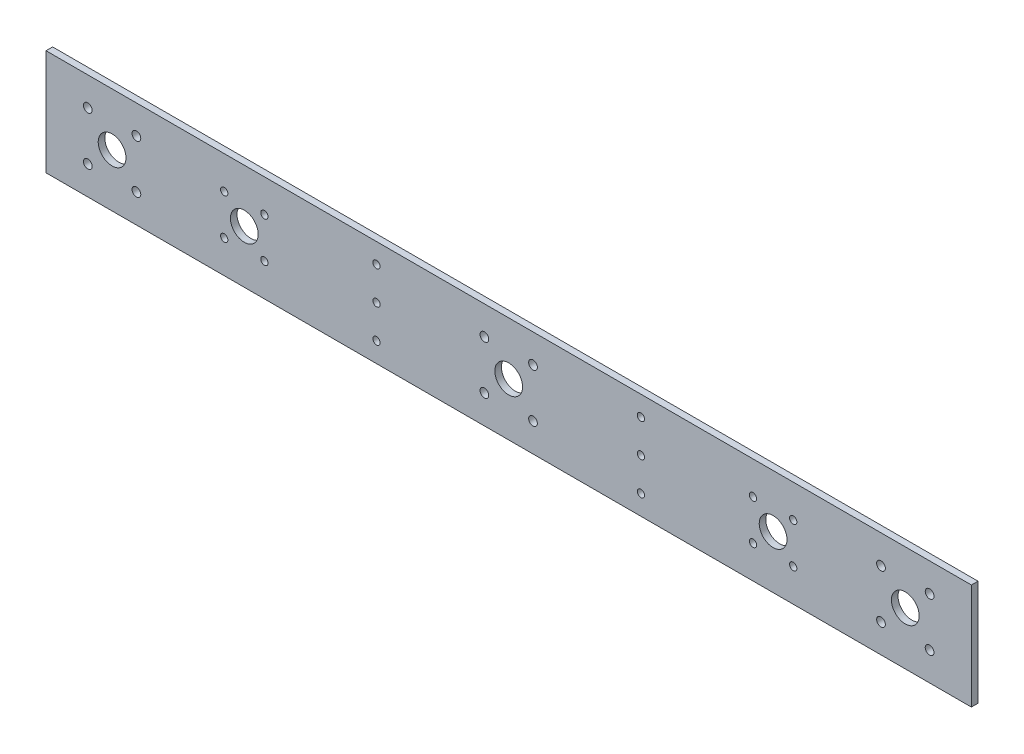
SolidWorks part; units mm, degrees
ref_plane "前视基准面" through (0, 0, 0) normal (0, 0, 1) x (1, 0, 0)
ref_plane "上视基准面" through (0, 0, 0) normal (0, 1, 0) x (1, 0, 0)
ref_plane "右视基准面" through (0, 0, 0) normal (1, 0, 0) x (0, 0, -1)
sketch "草图1" plane through (0, 0, 0) normal (0, 0, 1) x (1, 0, 0)
  line L0 (0, 40) -> (0, 0) construction
  line L1 (400, -40) -> (-400, -40)
  line L2 (400, -40) -> (400, 40)
  line L3 (400, 40) -> (-400, 40)
  line L4 (-400, -40) -> (-400, 40)
  line L5 (400, -40) -> (-400, 40) construction
  line L6 (400, 40) -> (-400, -40) construction
  line L7 (0, 0) -> (-400, 0) construction
  line L9 (-281.6152, -18.3848) -> (-318.3848, -18.3848) construction
  line L10 (-281.6152, -18.3848) -> (-281.6152, 18.3848) construction
  line L11 (-281.6152, 18.3848) -> (-318.3848, 18.3848) construction
  line L12 (-318.3848, -18.3848) -> (-318.3848, 18.3848) construction
  line L13 (-281.6152, -18.3848) -> (-318.3848, 18.3848) construction
  line L14 (-281.6152, 18.3848) -> (-318.3848, -18.3848) construction
  line L15 (-184.7972, -15.2028) -> (-215.2028, -15.2028) construction
  line L16 (-184.7972, -15.2028) -> (-184.7972, 15.2028) construction
  line L17 (-184.7972, 15.2028) -> (-215.2028, 15.2028) construction
  line L18 (-215.2028, -15.2028) -> (-215.2028, 15.2028) construction
  line L19 (-184.7972, -15.2028) -> (-215.2028, 15.2028) construction
  line L20 (-184.7972, 15.2028) -> (-215.2028, -15.2028) construction
  line L21 (18.3848, -18.3848) -> (-18.3848, -18.3848) construction
  line L22 (18.3848, -18.3848) -> (18.3848, 18.3848) construction
  line L23 (18.3848, 18.3848) -> (-18.3848, 18.3848) construction
  line L24 (-18.3848, -18.3848) -> (-18.3848, 18.3848) construction
  line L25 (18.3848, -18.3848) -> (-18.3848, 18.3848) construction
  line L26 (18.3848, 18.3848) -> (-18.3848, -18.3848) construction
  line L27 (-106.3908, -25) -> (-93.6092, -25) construction
  line L28 (-106.3908, -25) -> (-106.3908, 25) construction
  line L29 (-106.3908, 25) -> (-93.6092, 25) construction
  line L30 (-93.6092, -25) -> (-93.6092, 25) construction
  line L31 (-106.3908, -25) -> (-93.6092, 25) construction
  line L32 (-106.3908, 25) -> (-93.6092, -25) construction
  circle A0 centre (-318.3848, 18.3848) radius 3.3
  circle A1 centre (-281.6152, 18.3848) radius 3.3
  circle A2 centre (-281.6152, -18.3848) radius 3.3
  circle A3 centre (-318.3848, -18.3848) radius 3.3
  circle A4 centre (-215.2028, 15.2028) radius 2.75
  circle A5 centre (-184.7972, 15.2028) radius 2.75
  circle A6 centre (-184.7972, -15.2028) radius 2.75
  circle A7 centre (-215.2028, -15.2028) radius 2.75
  circle A8 centre (-200, 0) radius 10.5
  circle A9 centre (-18.3848, 18.3848) radius 3.3
  circle A10 centre (18.3848, 18.3848) radius 3.3
  circle A11 centre (18.3848, -18.3848) radius 3.3
  circle A12 centre (-18.3848, -18.3848) radius 3.3
  circle A13 centre (215.2028, -15.2028) radius 2.75
  circle A14 centre (184.7972, -15.2028) radius 2.75
  circle A15 centre (184.7972, 15.2028) radius 2.75
  circle A16 centre (215.2028, 15.2028) radius 2.75
  circle A17 centre (200, 0) radius 10.5
  circle A18 centre (318.3848, -18.3848) radius 3.3
  circle A19 centre (281.6152, -18.3848) radius 3.3
  circle A20 centre (281.6152, 18.3848) radius 3.3
  circle A21 centre (318.3848, 18.3848) radius 3.3
  circle A22 centre (-100, 25) radius 2.75
  circle A23 centre (-100, 0) radius 2.75
  circle A24 centre (-100, -25) radius 2.75
  circle A25 centre (100, -25) radius 2.75
  circle A26 centre (100, 0) radius 2.75
  circle A27 centre (100, 25) radius 2.75
  circle A28 centre (-300, 0) radius 10.5
  circle A29 centre (0, 0) radius 10.5
  circle A30 centre (300, 0) radius 10.5
  point P0 (0, 0)
  point P9 (-300, 0)
  point P10 (-200, 0)
  point P11 (-200, 0)
  point P12 (0, 0)
  point P14 (-300, 0)
  point P58 (-100, 0)
  dimension "D7" = 6.6
  dimension "D8" = 5.5
  dimension "D9" = 21
  dimension "D11" = 5.5
  dimension "D12" = 25
  dimension "D14" = 21
  dimension "D15" = 21
  dimension "D1" = 800
  dimension "D2" = 80
  dimension "D3" = 200
  dimension "D4" = 100
  dimension "D5" = 52
  dimension "D6" = 43
  dimension "D10" = 52
  dimension "D13" = 100
extrude "凸台-拉伸1" add sketch "草图1" along normal blind 5
sketch "草图2" plane through (0, 0, 5) normal (0, 0, 1) x (1, 0, 0)
  line L0 (-400, -40) -> (400, -40) construction
  line L1 (-400, 40) -> (-350, 40)
  line L2 (-400, 40) -> (-400, -40)
  line L3 (-400, -40) -> (-350, -40)
  line L4 (-350, 40) -> (-350, -40)
  line L6 (400, 40) -> (350, 40)
  line L7 (400, 40) -> (400, -40)
  line L8 (400, -40) -> (350, -40)
  line L9 (350, 40) -> (350, -40)
  dimension "D1" = 50
extrude "切除-拉伸1" cut sketch "草图2" against normal through all
